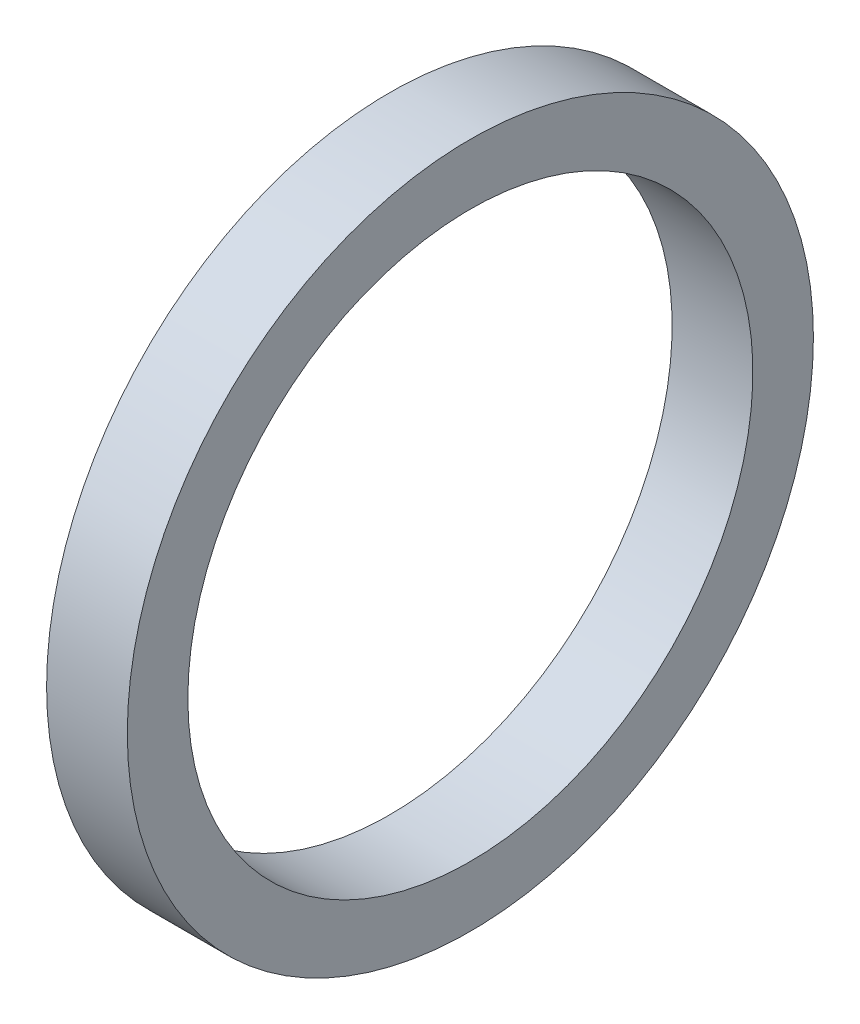
SolidWorks part; units mm, degrees
ref_plane "前视基准面" through (0, 0, 0) normal (0, 0, 1) x (1, 0, 0)
ref_plane "上视基准面" through (0, 0, 0) normal (0, 1, 0) x (1, 0, 0)
ref_plane "右视基准面" through (0, 0, 0) normal (1, 0, 0) x (0, 0, -1)
other "Configuration Table"
sketch "草图1" plane through (0, 0, 0) normal (0, 0, 1) x (1, 0, 0)
  line L0 (-59.6593, 0) -> (89.3294, 0) construction
  line L1 (0, 0) -> (0, 35)
  line L2 (0, 35) -> (10, 35)
  line L3 (10, 35) -> (10, 42.5)
  line L4 (10, 42.5) -> (0, 42.5)
  line L5 (0, 42.5) -> (0, 35)
  dimension "D1" = 35
  dimension "D2" = 7.5
  dimension "D3" = 10
revolve "旋转1" add sketch "草图1" angle 360 about L0
